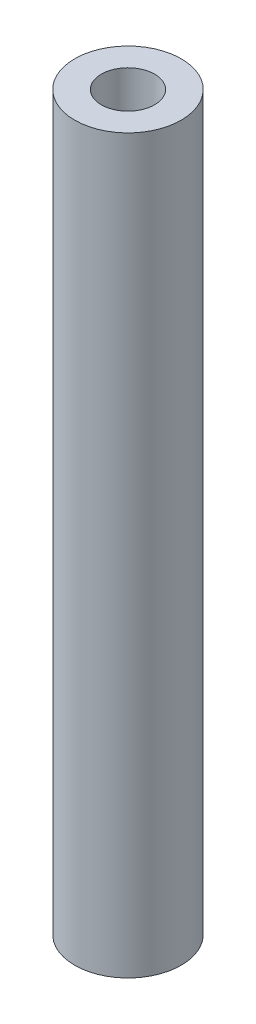
SolidWorks part; units mm, degrees
material "6061 Alloy"
ref_plane "Front Plane" through (0, 0, 0) normal (0, 0, 1) x (1, 0, 0)
ref_plane "Top Plane" through (0, 0, 0) normal (0, 1, 0) x (1, 0, 0)
ref_plane "Right Plane" through (0, 0, 0) normal (1, 0, 0) x (0, 0, -1)
sketch "Sketch1" plane through (0, 0, 0) normal (0, 1, 0) x (1, 0, 0)
  circle A0 centre (0, 0) radius 2.54
  circle A1 centre (0, 0) radius 1.27
  dimension "D1" = 2.54
  dimension "D2" = 5.08
extrude "Boss-Extrude1" add sketch "Sketch1" along normal mid plane 34.925
